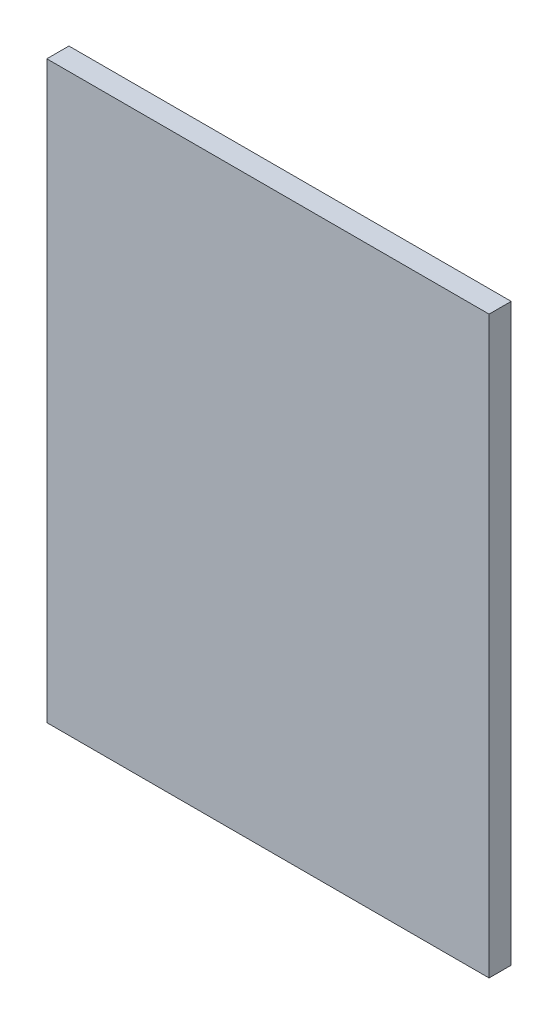
SolidWorks part; units mm, degrees
material "1060 Alloy"
ref_plane "Front Plane" through (0, 0, 0) normal (0, 0, 1) x (1, 0, 0)
ref_plane "Top Plane" through (0, 0, 0) normal (0, 1, 0) x (1, 0, 0)
ref_plane "Right Plane" through (0, 0, 0) normal (1, 0, 0) x (0, 0, -1)
sketch "Sketch1" plane through (0, 0, 0) normal (0, 0, 1) x (1, 0, 0)
  line L1 (-33.4866, 51.6858) -> (66.5134, 51.6858)
  line L2 (-33.4866, 51.6858) -> (-33.4866, -78.3142)
  line L3 (-33.4866, -78.3142) -> (66.5134, -78.3142)
  line L4 (66.5134, 51.6858) -> (66.5134, -78.3142)
  dimension "D1" = 130
  dimension "D2" = 100
extrude "Boss-Extrude1" add sketch "Sketch1" along normal blind 5
